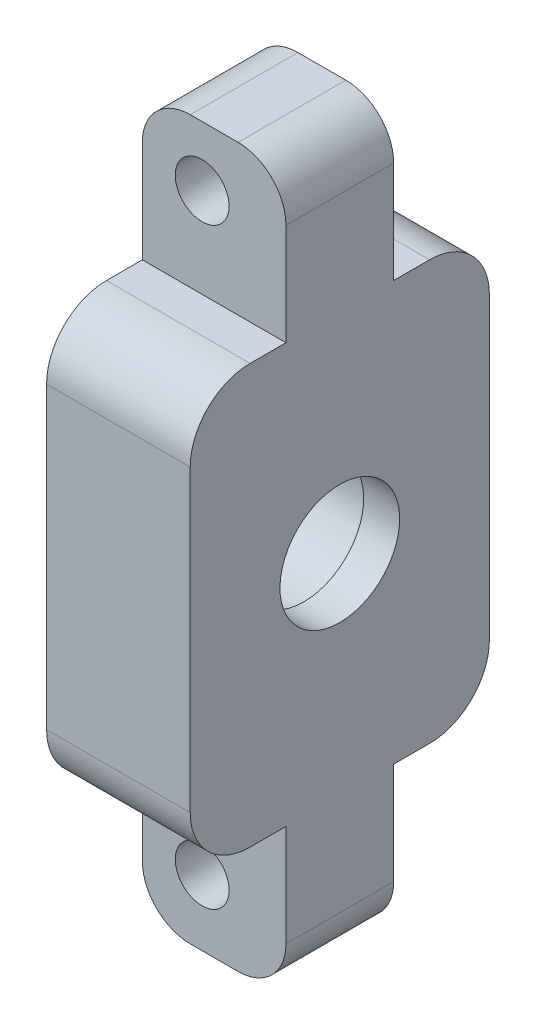
SolidWorks part; units mm, degrees
ref_plane "Front Plane" through (0, 0, 0) normal (0, 0, 1) x (1, 0, 0)
ref_plane "Top Plane" through (0, 0, 0) normal (0, 1, 0) x (1, 0, 0)
ref_plane "Right Plane" through (0, 0, 0) normal (1, 0, 0) x (0, 0, -1)
sketch "Sketch2" plane through (0, 0, 0) normal (0, 0, 1) x (1, 0, 0)
  line L1 (-6, 30) -> (6, 30)
  line L2 (-6, 30) -> (-6, -30)
  line L3 (-6, -30) -> (6, -30)
  line L4 (6, 30) -> (6, -30)
  line L5 (-6, 30) -> (6, -30) construction
  line L6 (-6, -30) -> (6, 30) construction
  point P0 (0, 0)
  dimension "D1" = 60
  dimension "D2" = 12
extrude "Boss-Extrude1" add sketch "Sketch2" along normal mid plane 25
sketch "Sketch3" plane through (6, 0, 0) normal (1, 0, 0) x (0, 0, -1)
  line L0 (-12.5, 30) -> (12.5, 30) construction
  line L2 (-4.5, 30) -> (-4.5, 17.5)
  line L4 (4.5, 30) -> (4.5, 17.5)
  line L9 (55, 0) -> (-55, 0) construction
  line L10 (-12.5, 30) -> (-4.5, 30)
  line L11 (-12.5, 30) -> (-12.5, 17.5)
  line L12 (-12.5, 17.5) -> (-4.5, 17.5)
  line L13 (-4.5, 30) -> (-4.5, 17.5)
  line L14 (12.5, 30) -> (4.5, 30)
  line L15 (12.5, 30) -> (12.5, 17.5)
  line L16 (12.5, 17.5) -> (4.5, 17.5)
  line L17 (4.5, 30) -> (4.5, 17.5)
  line L18 (4.5, -30) -> (4.5, -17.5)
  line L19 (12.5, -17.5) -> (4.5, -17.5)
  line L20 (12.5, -30) -> (12.5, -17.5)
  line L21 (12.5, -30) -> (4.5, -30)
  line L22 (-4.5, -30) -> (-4.5, -17.5)
  line L23 (-12.5, -17.5) -> (-4.5, -17.5)
  line L24 (-12.5, -30) -> (-12.5, -17.5)
  line L25 (-12.5, -30) -> (-4.5, -30)
  line L26 (4.5, -30) -> (4.5, -17.5)
  line L27 (-4.5, -30) -> (-4.5, -17.5)
  line M4 (12.5, -30) -> (12.5, 30)
  line M5 (12.5, 30) -> (-12.5, 30)
  line M6 (-12.5, 30) -> (-12.5, -30)
  line M7 (-12.5, -30) -> (12.5, -30)
  dimension "D1" = 9
extrude "Cut-Extrude1" cut sketch "Sketch3" against normal through all contours L23 L22 M6 M7 | L19 L18 M4 M7 | L16 L4 M4 M5 | L12 L2 M6 M5
sketch "Sketch4" plane through (0, 0, 4.5) normal (0, 0, 1) x (1, 0, 0)
  line L0 (-6, -30) -> (6, -30) construction
  line L1 (-6, 30) -> (-6, 17.5) construction
  line L2 (-6, -30) -> (-6, -17.5) construction
  circle A0 centre (-1, 25) radius 2.25
  circle A1 centre (-1, -24.5) radius 2.25
  dimension "D1" = 4.5
  dimension "D2" = 4.5
  dimension "D3" = 49.5
  dimension "D4" = 5.5
  dimension "D5" = 5
  dimension "D6" = 5
extrude "Cut-Extrude2" cut sketch "Sketch4" against normal through all
fillet "Fillet1" radius 5 4 edges at (0, -17.5, 12.5) (0, -17.5, -12.5) (0, 17.5, -12.5) (0, 17.5, 12.5)
fillet "Fillet2" radius 4 4 edges at (6, -30, 0) (-6, -30, 0) (-6, 30, 0) (6, 30, 0)
sketch "Sketch5" plane through (-6, 0, 0) normal (-1, 0, 0) x (0, 0, 1)
  circle A0 centre (0, 0) radius 5
  dimension "D1" = 10
extrude "Cut-Extrude3" cut sketch "Sketch5" against normal blind 4 from offset 8 offset against normal yes
sketch "Sketch6" plane through (-6, 0, 0) normal (-1, 0, 0) x (0, 0, 1)
  circle A0 centre (0, 0) radius 7.5
  dimension "D1" = 15
extrude "Cut-Extrude4" cut sketch "Sketch6" against normal blind 4
sketch "Sketch8" plane through (-2, 0, 0) normal (-1, 0, 0) x (0, 0, 1)
  circle A0 centre (0, 0) radius 5.5
  dimension "D1" = 11
extrude "Cut-Extrude6" cut sketch "Sketch8" against normal blind 5
